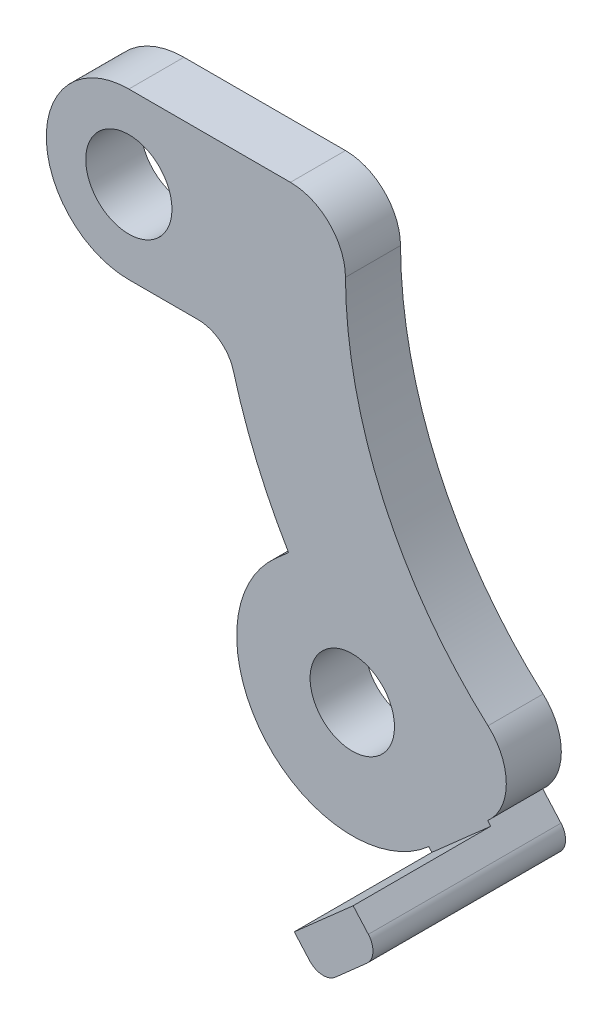
SolidWorks part; units mm, degrees
ref_plane "Front Plane" through (0, 0, 0) normal (0, 0, 1) x (1, 0, 0)
ref_plane "Top Plane" through (0, 0, 0) normal (0, 1, 0) x (1, 0, 0)
ref_plane "Right Plane" through (0, 0, 0) normal (1, 0, 0) x (0, 0, -1)
sketch "Sketch1" plane through (0, 0, -130.2439) normal (0, 0, 1) x (1, 0, 0)
  line L0 (-15.7081, 37.5725) -> (-15.0101, 38.1894) construction
  line L6 (-15.7081, 37.5725) -> (-15.0101, 38.1894)
  line L21 (1.2909, 35.7798) -> (-7.3644, 28.1309) construction
  line L22 (-17.5363, 52.8349) -> (-17.5363, 78.2517)
  line L23 (-1.1666, 35.6099) -> (-8.3577, 29.2549)
  line L26 (-14.7148, 36.4485) -> (-13.0642, 37.9072)
  line L31 (-4.1549, 30.9672) -> (-7.3644, 28.1309)
  line L35 (-23.7161, 46.719) -> (-19.9422, 46.719)
  line L36 (-23.7161, 55.719) -> (-14.9089, 55.719)
  arc A21 (-11.5363, 35.1017) -> (-11.5363, 30.6017) centre (-11.5363, 32.8517) ccw construction
  arc A22 (30.9499, 61.6319) -> (-1.1666, 35.6099) centre (11.4637, 52.8517) ccw
  arc A23 (-17.5363, 52.8349) -> (-13.0642, 37.9072) centre (9.6137, 52.8349) ccw
  arc A24 (-14.7148, 36.4485) -> (-8.3577, 29.2549) centre (-11.5363, 32.8517) ccw
  arc A25 (-9.8393, 51.1233) -> (-0.3376, 35.0322) centre (11.4637, 52.8517) ccw
  arc A28 (-11.5363, 30.6017) -> (-11.5363, 35.1017) centre (-11.5363, 32.8517) ccw construction
  arc A29 (-11.5363, 35.1017) -> (-11.5363, 30.6017) centre (-11.5363, 32.8517) ccw
  arc A30 (-11.5363, 30.6017) -> (-11.5363, 35.1017) centre (-11.5363, 32.8517) ccw
  arc A31 (-15.7081, 37.5725) -> (-7.3644, 28.1309) centre (-11.5363, 32.8517) ccw construction
  arc A32 (-19.9422, 46.719) -> (-18.0136, 45.2485) centre (-19.9422, 44.719) cw
  arc A33 (-15.7081, 37.5725) -> (-7.3644, 28.1309) centre (-11.5363, 32.8517) ccw
  circle A35 centre (-23.7161, 51.219) radius 2.25
  arc A36 (-23.7161, 55.719) -> (-23.7161, 46.719) centre (-23.7161, 51.219) ccw
  arc A40 (-11.909, 52.7341) -> (-4.1388, 35.4489) centre (11.4637, 52.8517) ccw
  arc A41 (-18.0136, 45.2485) -> (-15.0101, 38.1894) centre (9.6137, 52.8349) ccw
  arc A42 (-19.0363, 52.8517) -> (-15.0101, 38.1894) centre (9.6137, 52.8349) ccw construction
  arc A43 (-11.8327, 50.9616) -> (-1.4419, 33.3648) centre (11.4637, 52.8517) ccw construction
  arc A44 (-4.1388, 35.4489) -> (-4.1549, 30.9672) centre (-6.1415, 33.2152) cw
  arc A45 (-11.909, 52.7341) -> (-14.9089, 55.719) centre (-14.9089, 52.719) ccw
  circle A46 centre (-23.7161, 51.219) radius 2.35
  circle A47 centre (-11.5363, 32.8517) radius 2.3
  point P25 (-9.7161, 55.719)
  line M29 (-19.0363, 78.2517) -> (-19.0363, 52.8517)
  arc M30 (-19.0363, 52.8517) -> (-15.0101, 38.1894) centre (9.6137, 52.8349) ccw
  line M31 (-15.0101, 38.1894) -> (-15.7081, 37.5725)
  arc M32 (-15.7081, 37.5725) -> (-7.3644, 28.1309) centre (-11.5363, 32.8517) ccw
  line M33 (-7.3644, 28.1309) -> (1.2909, 35.7798)
  circle M35 centre (-11.5363, 32.8517) radius 2.25
  dimension "D1" = 1.5
  dimension "D2" = 2
  dimension "D3" = 3
  dimension "D4" = 2
  dimension "D5" = 4.5
  dimension "D6" = 14
  dimension "D7" = 4.7
  dimension "D8" = 4.6
extrude "Boss-Extrude2" add sketch "Sketch1" along normal blind 3 contours L36 A36 L35 A32 A35 M30 M29 | A40 A45 L36 A44 M29 M30 M31 M32 M33 M35
sketch "Sketch2" plane through (-17.188, 19.4496, 0) normal (0.6622, -0.7493, 0) x (0.7493, 0.6622, 0)
  line L4 (13.1099, -130.2439) -> (17.3931, -130.2439)
  line L5 (17.3931, -130.2439) -> (17.3931, -127.2439)
  line L6 (17.3931, -127.2439) -> (13.1099, -127.2439)
  line L7 (13.1099, -127.2439) -> (13.1099, -130.2439)
  line L8 (13.1099, -130.2439) -> (17.3931, -130.2439)
  line L9 (17.3931, -130.2439) -> (17.3931, -127.2439)
  line L10 (17.3931, -127.2439) -> (13.1099, -127.2439)
  line L11 (13.1099, -127.2439) -> (13.1099, -130.2439)
  dimension "D1" = 0
extrude "Boss-Extrude3" add sketch "Sketch2" along normal blind 2.5
sketch "Sketch3" plane through (0, 0, -127.2439) normal (0, 0, 1) x (1, 0, 0)
  line L0 (-7.3644, 28.1309) -> (-4.1549, 30.9672)
  line L1 (-4.1549, 30.9672) -> (-2.4994, 29.0939)
  line L2 (-2.4994, 29.0939) -> (-5.7089, 26.2576)
  line L3 (-5.7089, 26.2576) -> (-7.3644, 28.1309)
extrude "Boss-Extrude4" add sketch "Sketch3" along normal blind 7.5
fillet "Fillet1" radius 1 2 edges at (-5.7089, 26.2576, -124.9939) (-2.4994, 29.0939, -124.9939)
sketch "Sketch4" plane through (-17.188, 19.4496, 0) normal (-0.6622, 0.7493, 0) x (0.7493, 0.6622, 0)
  line L4 (17.3931, 127.2439) -> (13.1099, 127.2439)
  line L5 (13.1099, 127.2439) -> (13.1099, 119.7439)
  line L6 (13.1099, 119.7439) -> (17.3931, 119.7439)
  line L7 (17.3931, 119.7439) -> (17.3931, 127.2439)
  line L8 (17.3931, 127.2439) -> (13.1099, 127.2439)
  line L9 (13.1099, 127.2439) -> (13.1099, 119.7439)
  line L10 (13.1099, 119.7439) -> (17.3931, 119.7439)
  line L11 (17.3931, 119.7439) -> (17.3931, 127.2439)
  dimension "D1" = 0
extrude "Cut-Extrude1" cut sketch "Sketch4" against normal blind 0.25
